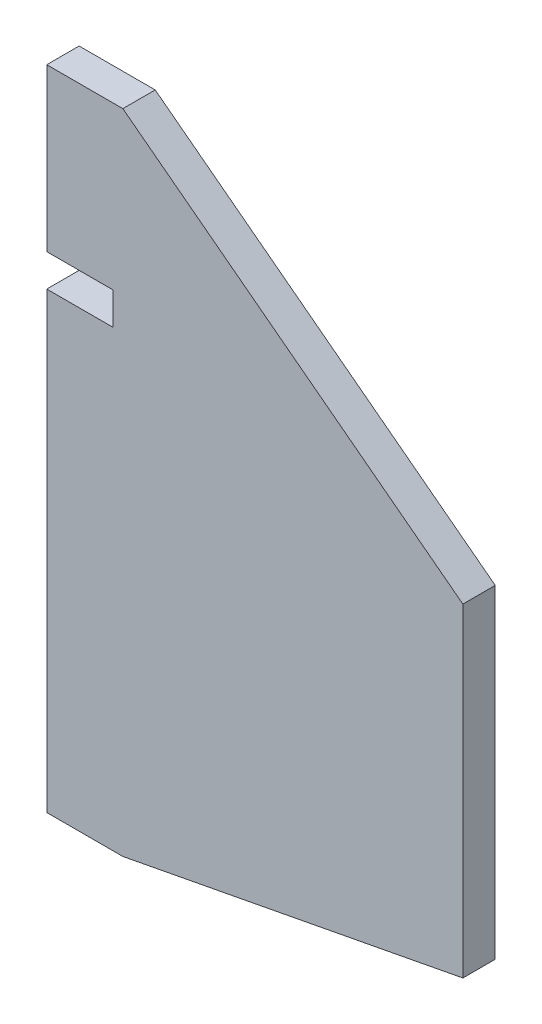
SolidWorks part; units mm, degrees
material "Beech"
ref_plane "Front Plane" through (0, 0, 0) normal (0, 0, 1) x (1, 0, 0)
ref_plane "Top Plane" through (0, 0, 0) normal (0, 1, 0) x (1, 0, 0)
ref_plane "Right Plane" through (0, 0, 0) normal (1, 0, 0) x (0, 0, -1)
sketch "Sketch2" plane through (0, 0, 0) normal (0, 0, 1) x (1, 0, 0)
  line L0 (0, 0) -> (11.938, 0)
  line L1 (11.938, 0) -> (65.278, 10.16)
  line L2 (65.278, 10.16) -> (65.278, 60.96)
  line L3 (65.278, 60.96) -> (11.938, 101.6)
  line L4 (11.938, 101.6) -> (0, 101.6)
  line L5 (0, 101.6) -> (0, 0)
  dimension "D1" = 101.6
  dimension "D2" = 53.34
  dimension "D3" = 50.8
  dimension "D4" = 40.64
  dimension "D5" = 11.938
extrude "Boss-Extrude1" add sketch "Sketch2" along normal blind 5.08
sketch "Sketch3" plane through (0, 0, 5.08) normal (0, 0, 1) x (1, 0, 0)
  line L0 (0, 101.6) -> (0, 0) construction
  line L1 (0, 76.2) -> (10.414, 76.2)
  line L2 (0, 76.2) -> (0, 71.12)
  line L3 (0, 71.12) -> (10.414, 71.12)
  line L4 (10.414, 76.2) -> (10.414, 71.12)
  line L5 (11.938, 101.6) -> (0, 101.6) construction
  dimension "D1" = 5.08
  dimension "D2" = 10.414
  dimension "D3" = 25.4
extrude "Cut-Extrude1" cut sketch "Sketch3" against normal through all
